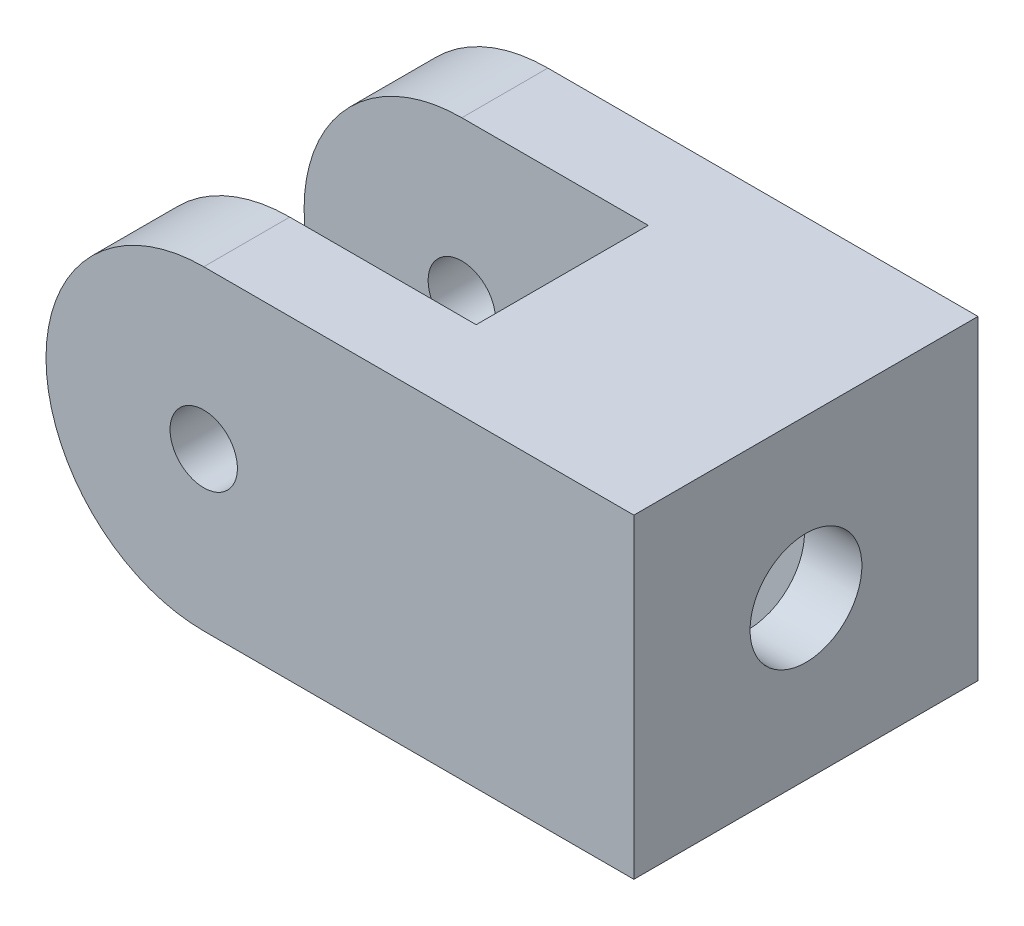
SolidWorks part; units mm, degrees
ref_plane "Front Plane" through (0, 0, 0) normal (0, 0, 1) x (1, 0, 0)
ref_plane "Top Plane" through (0, 0, 0) normal (0, 1, 0) x (1, 0, 0)
ref_plane "Right Plane" through (0, 0, 0) normal (1, 0, 0) x (0, 0, -1)
ref_plane "Plane1" through (0, 0, -24) normal (0, 0, -1) x (-1, 0, 0)
sketch "Sketch1" plane through (0, 0, -24) normal (0, 0, -1) x (-1, 0, 0)
  line L0 (0, 11) -> (-30, 11)
  line L1 (-30, 11) -> (-30, -11)
  line L2 (-30, -11) -> (0, -11)
  arc A0 (0, -11) -> (0, 11) centre (0, 0) ccw
extrude "Boss-Extrude1" add sketch "Sketch1" against normal blind 24
sketch "Sketch2" plane through (0, 11, 0) normal (0, 1, 0) x (-1, 0, 0)
  line L0 (17.1108, -18) -> (17.1108, -6)
  line L1 (17.1108, -6) -> (-13, -6)
  line L2 (-13, -6) -> (-13, -18)
  line L3 (-13, -18) -> (17.1108, -18)
  line L4 (-35.3701, -12) -> (15.4323, -12) construction
  dimension "D1" = 12
  dimension "D2" = 30.1108
extrude "Cut-Extrude1" cut sketch "Sketch2" against normal through all
ref_plane "Plane2" through (19.2, 0, 0) normal (-1, 0, 0) x (0, -1, 0)
sketch "Sketch3" plane through (19.2, 0, 0) normal (-1, 0, 0) x (0, -1, 0)
  line L0 (11, -18.5) -> (11, -5.5)
  line L1 (11, -5.5) -> (-3.7528, -5.5)
  line L2 (-3.7528, -5.5) -> (-7.5056, -12)
  line L3 (-7.5056, -12) -> (-3.7528, -18.5)
  line L4 (-3.7528, -18.5) -> (11, -18.5)
extrude "Cut-Extrude2" cut sketch "Sketch3" against normal blind 6.8
hole_wizard "Ø7.8 (7.8) Diameter Hole1" positions "Sketch5" profile "Sketch4" hole size "Ø7.8" standard "ANSI Metric"
sketch "Sketch5" plane through (13, 0, 0) normal (-1, 0, 0) x (0, 0, 1)
  point P0 (-12, 0)
sketch "Sketch4" plane through (13, 0, -12) normal (0, 1, 0) x (0, 0, 1)
  line L0 (0, 0) -> (0, 6.2)
  line L1 (0, 6.2) -> (3.9, 6.2)
  line L2 (3.9, 6.2) -> (3.9, 0)
  line L5 (3.9, 0) -> (0, 0)
  line L11 (0, -6.35) -> (0, 107.95) construction
  dimension "Thru Hole Dia." = 7.8
  dimension "Thru Hole Depth" = 6.2
hole_wizard "Ø7.8 (7.8) Diameter Hole2" positions "Sketch7" profile "Sketch6" hole size "Ø7.8" standard "ANSI Metric" end condition through all
sketch "Sketch7" plane through (26, 0, 0) normal (-1, 0, 0) x (0, 0, 1)
  point P0 (-12, 0)
sketch "Sketch6" plane through (26, 0, -12) normal (0, 1, 0) x (0, 0, 1)
  line L0 (0, 0) -> (0, 4)
  line L1 (0, 4) -> (3.9, 4)
  line L2 (3.9, 4) -> (3.9, 0)
  line L5 (3.9, 0) -> (0, 0)
  line L11 (0, -6.35) -> (0, 107.95) construction
  dimension "Thru Hole Dia." = 7.8
  dimension "Thru Hole Depth" = 4
hole_wizard "Ø4.7 (4.7) Diameter Hole1" positions "Sketch9" profile "Sketch8" hole size "Ø4.7" standard "ANSI Metric"
sketch "Sketch9" plane through (0, 0, -24) normal (0, 0, -1) x (-1, 0, 0)
  point P0 (0, 0)
sketch "Sketch8" plane through (0, 0, -24) normal (1, 0, 0) x (0, 1, 0)
  line L0 (0, 0) -> (0, 6)
  line L1 (0, 6) -> (2.35, 6)
  line L2 (2.35, 6) -> (2.35, 0)
  line L5 (2.35, 0) -> (0, 0)
  line L11 (0, -6.35) -> (0, 107.95) construction
  dimension "Thru Hole Dia." = 4.7
  dimension "Thru Hole Depth" = 6
hole_wizard "Ø4.7 (4.7) Diameter Hole2" positions "Sketch11" profile "Sketch10" hole size "Ø4.7" standard "ANSI Metric" end condition through all
sketch "Sketch11" plane through (0, 0, -6) normal (0, 0, -1) x (-1, 0, 0)
  point P0 (0, 0)
sketch "Sketch10" plane through (0, 0, -6) normal (1, 0, 0) x (0, 1, 0)
  line L0 (0, 0) -> (0, 6)
  line L1 (0, 6) -> (2.35, 6)
  line L2 (2.35, 6) -> (2.35, 0)
  line L5 (2.35, 0) -> (0, 0)
  line L11 (0, -6.35) -> (0, 107.95) construction
  dimension "Thru Hole Dia." = 4.7
  dimension "Thru Hole Depth" = 6
